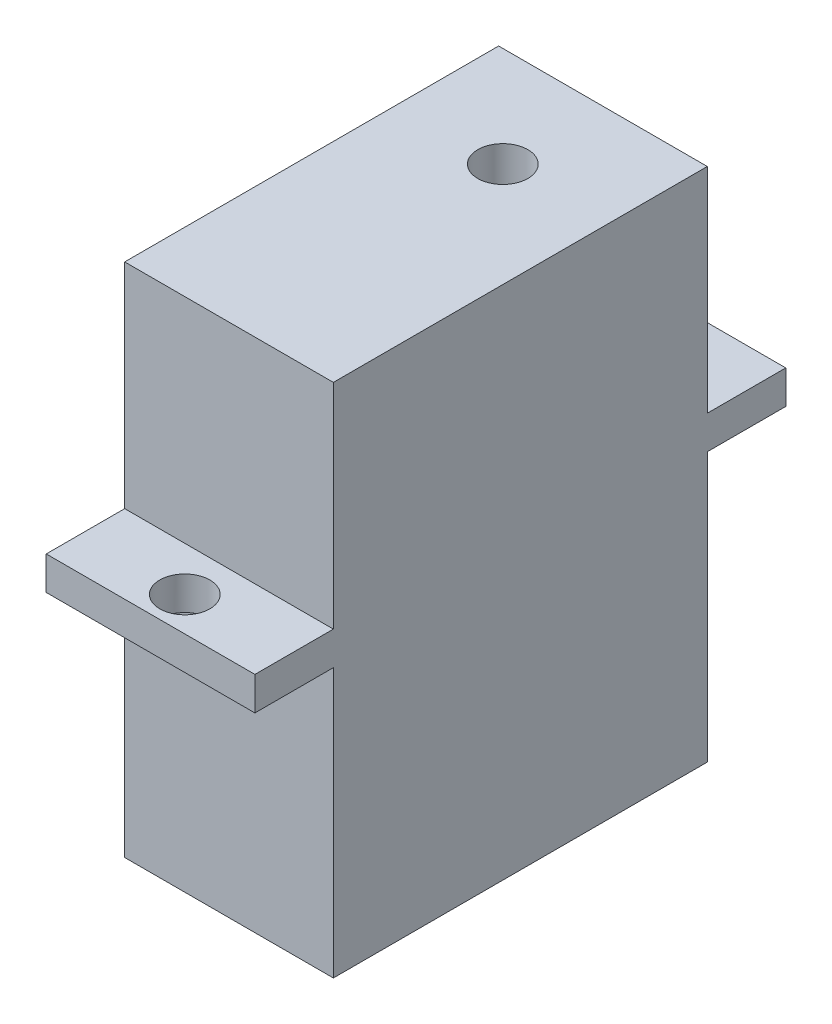
SolidWorks part; units mm, degrees
ref_plane "前视基准面" through (0, 0, 0) normal (0, 0, 1) x (1, 0, 0)
ref_plane "上视基准面" through (0, 0, 0) normal (0, 1, 0) x (1, 0, 0)
ref_plane "右视基准面" through (0, 0, 0) normal (1, 0, 0) x (0, 0, -1)
sketch "草图1" plane through (0, 0, 0) normal (0, 1, 0) x (1, 0, 0)
  line L1 (-6.25, 11.2) -> (6.25, 11.2)
  line L2 (-6.25, 11.2) -> (-6.25, -11.2)
  line L3 (-6.25, -11.2) -> (6.25, -11.2)
  line L4 (6.25, 11.2) -> (6.25, -11.2)
  line L5 (-6.25, 11.2) -> (6.25, -11.2) construction
  line L6 (-6.25, -11.2) -> (6.25, 11.2) construction
  point P0 (0, 0)
  dimension "D1" = 12.5
  dimension "D2" = 22.4
extrude "凸台-拉伸1" add sketch "草图1" along normal blind 30.9
sketch "草图4" plane through (6.25, 0, 0) normal (1, 0, 0) x (0, 0, -1)
  line L0 (0, 0) -> (0, 16.1) construction
  line L2 (-15.9, 16.1) -> (15.9, 16.1)
  line L3 (-15.9, 16.1) -> (-15.9, 18.1)
  line L4 (-15.9, 18.1) -> (15.9, 18.1)
  line L5 (15.9, 16.1) -> (15.9, 18.1)
  dimension "D1" = 16.1
  dimension "D2" = 2
  dimension "2" = 31.8
extrude "凸台-拉伸2" add sketch "草图4" against normal blind 12.5
sketch "草图6" plane through (0, 18.1, 0) normal (0, 1, 0) x (1, 0, 0)
  line L0 (0, -13.85) -> (0, 13.85) construction
  circle A2 centre (0, 13.85) radius 1.5
  circle A3 centre (0, -13.85) radius 1.5
  point P3 (0, 0)
  dimension "D1" = 27.7
  dimension "D2" = 3
  dimension "D3" = 3
extrude "切除-拉伸2" cut sketch "草图6" against normal through all
sketch "草图7" plane through (0, 30.9, 0) normal (0, 1, 0) x (1, 0, 0)
  line L0 (0, 11.2) -> (0, 5.2) construction
  line L1 (6.25, 11.2) -> (-6.25, 11.2) construction
  circle A0 centre (0, 5.2) radius 1.5
  dimension "D2" = 3
  dimension "D1" = 6
extrude "切除-拉伸3" cut sketch "草图7" against normal blind 3
